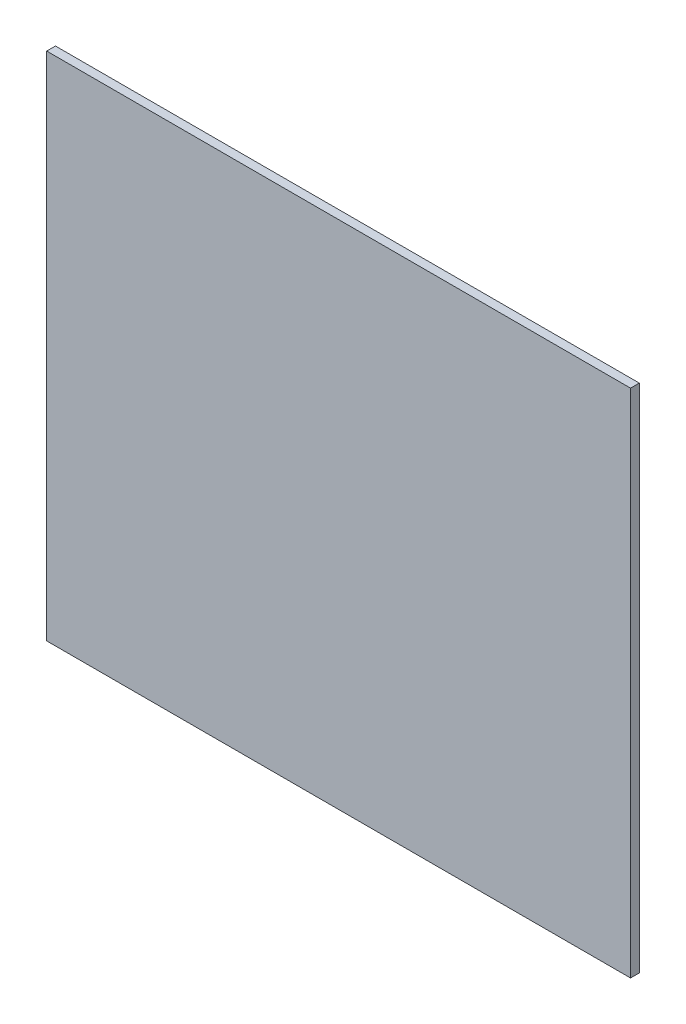
SolidWorks part; units mm, degrees
material "Custom Plastic"
ref_plane "Front Plane" through (0, 0, 0) normal (0, 0, 1) x (1, 0, 0)
ref_plane "Top Plane" through (0, 0, 0) normal (0, 1, 0) x (1, 0, 0)
ref_plane "Right Plane" through (0, 0, 0) normal (1, 0, 0) x (0, 0, -1)
sketch "Sketch1" plane through (0, 0, 0) normal (0, 0, 1) x (1, 0, 0)
  line L1 (-100, -87.5) -> (100, -87.5)
  line L2 (-100, -87.5) -> (-100, 87.5)
  line L3 (-100, 87.5) -> (100, 87.5)
  line L4 (100, -87.5) -> (100, 87.5)
  line L5 (-100, -87.5) -> (100, 87.5) construction
  line L6 (-100, 87.5) -> (100, -87.5) construction
  point P0 (0, 0)
extrude "Boss-Extrude1" add sketch "Sketch1" along normal blind 3
